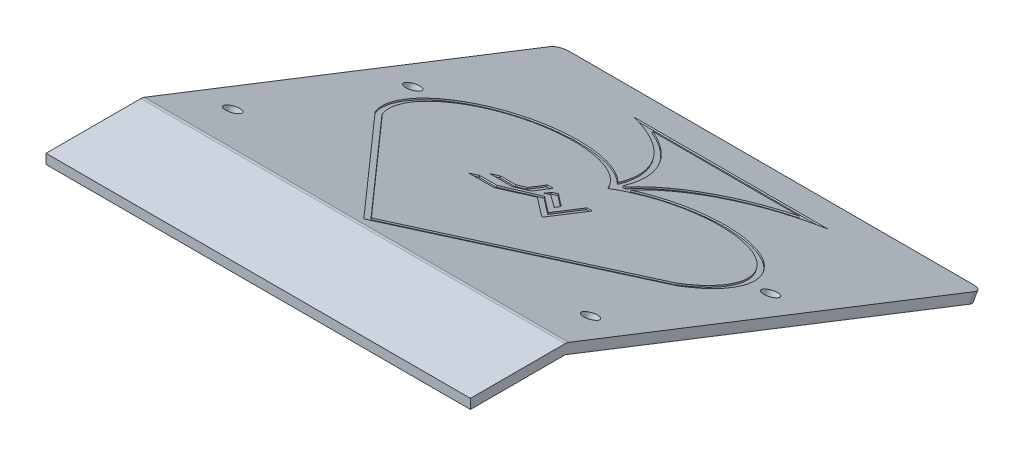
SolidWorks part; units mm, degrees
ref_plane "Plano frontal" through (0, 0, 0) normal (0, 0, 1) x (1, 0, 0)
ref_plane "Plano superior" through (0, 0, 0) normal (0, 1, 0) x (1, 0, 0)
ref_plane "Plano direito" through (0, 0, 0) normal (1, 0, 0) x (0, 0, -1)
sketch "Esboço1" plane through (0, 0, 0) normal (1, 0, 0) x (0, 0, -1)
  line L0 (0, 2) -> (19.99, 2)
  line L1 (19.61, 0) -> (0, 0)
  line L2 (19.99, 2) -> (106.12, -31.7453)
  line L3 (105.11, -33.4985) -> (19.61, 0)
  line L4 (0, 2) -> (0, 0)
  line L5 (106.12, -31.7453) -> (105.11, -33.4985)
  point P6 (0, 0)
  dimension "D1" = 19.61
  dimension "D2" = 19.99
  dimension "D3" = 105.11
  dimension "D4" = 106.12
  dimension "D5" = 2
  dimension "D6" = 31.7453
extrude "Ressalto-extrusão1" add sketch "Esboço1" along normal blind 87.78
sketch "Esboço2" plane through (0, 8.5236, -3.3395) normal (0, 0.9311, -0.3648) x (1, 0, 0)
  circle A0 centre (80.8, 30.5876) radius 1.55 construction
  circle A1 centre (80.8, 30.5876) radius 1.55
  circle A2 centre (6.8, 30.5876) radius 1.55 construction
  circle A3 centre (6.8, 30.5876) radius 1.55
  circle A4 centre (80.8, 70.5876) radius 1.55 construction
  circle A5 centre (80.8, 70.5876) radius 1.55
  circle A6 centre (6.8, 70.5876) radius 1.55 construction
  circle A7 centre (6.8, 70.5876) radius 1.55
extrude "Corte-extrusão1" cut sketch "Esboço2" against normal up to surface (2.0008 mm away) up to face at (43.89, -16.7493, -62.36)
fillet "Filete1" radius 2 2 edges at (0, -32.6219, -105.615) (87.78, -32.6219, -105.615)
fillet "Filete2" radius 2 1 edges at (43.89, 2, -19.99)
sketch "Esboço4" plane through (0, 8.5236, -3.3395) normal (0, 0.9311, -0.3648) x (1, 0, 0)
  line L0 (43.89, 21.5519) -> (43.89, 91.5519) construction
  line L1 (99.9585, 56.5537) -> (-12.1785, 56.55) construction
  line L2 (43.89, 21.5519) -> (13.5797, 56.5509)
  line L3 (43.89, 21.5519) -> (74.2015, 56.5529)
  line L4 (59.0454, 100.3019) -> (28.7346, 100.3019)
  line L5 (87.78, -0.7296) -> (0, -0.7296) construction
  line L6 (87.78, -0.7296) -> (0, -0.7296) construction
  line L7 (43.89, -0.7296) -> (43.89, 4.4324) construction
  line L8 (0, 108.3651) -> (0, 18.2607) construction
  line L9 (0, 108.3651) -> (0, 18.2607) construction
  circle A0 centre (43.89, 56.5519) radius 17.5 construction
  circle A1 centre (43.89, 39.0519) radius 17.5 construction
  circle A2 centre (28.7346, 47.8019) radius 17.5 construction
  circle A3 centre (59.0454, 47.8019) radius 17.5 construction
  arc A4 (43.89, 74.0519) -> (13.5797, 56.5509) centre (28.7346, 65.3019) ccw
  arc A5 (74.2015, 56.5529) -> (43.89, 74.0519) centre (59.0454, 65.3019) ccw
  circle A6 centre (28.7346, 30.3019) radius 17.5 construction
  circle A7 centre (59.0454, 30.3019) radius 17.5 construction
  circle A8 centre (43.89, 74.0519) radius 17.5 construction
  circle A9 centre (28.7346, 82.8019) radius 17.5 construction
  circle A10 centre (59.0454, 82.8019) radius 17.5 construction
  arc A11 (59.0454, 100.3019) -> (43.89, 74.0519) centre (74.2009, 74.0519) ccw
  arc A12 (43.89, 74.0519) -> (28.7346, 100.3019) centre (13.5791, 74.0519) ccw
  arc A13 (43.89, 74.0519) -> (43.89, 56.5519) centre (28.7346, 65.3019) cw construction
  arc A14 (28.7346, 47.8019) -> (43.89, 56.5519) centre (28.7346, 65.3019) ccw construction
  arc A15 (43.89, 56.5519) -> (28.7346, 47.8019) centre (28.7346, 65.3019) cw construction
  arc A16 (28.7346, 47.8019) -> (24.7873, 48.2528) centre (28.7346, 65.3019) cw construction
  arc A17 (17.9085, 51.5525) -> (24.7873, 48.2528) centre (28.7346, 65.3019) ccw construction
  arc A18 (24.7873, 48.2528) -> (17.9085, 51.5525) centre (28.7346, 65.3019) cw construction
  arc A19 (17.9085, 51.5525) -> (13.5797, 56.5509) centre (28.7346, 65.3019) cw construction
  arc A20 (13.5797, 56.5509) -> (17.9085, 51.5525) centre (28.7346, 65.3019) ccw construction
  arc A21 (43.89, 56.5519) -> (43.89, 74.0519) centre (28.7346, 65.3019) ccw construction
  arc A22 (43.89, 74.0519) -> (43.89, 56.5519) centre (59.0454, 65.3019) ccw construction
  arc A23 (43.89, 56.5519) -> (59.0454, 47.8019) centre (59.0454, 65.3019) ccw construction
  arc A24 (59.0454, 47.8019) -> (69.87, 51.5512) centre (59.0454, 65.3019) ccw construction
  arc A25 (69.87, 51.5512) -> (74.2015, 56.5529) centre (59.0454, 65.3019) ccw construction
  point P4 (43.89, 56.5519)
  point P28 (13.5797, 56.5509)
  point P34 (43.89, 56.5519)
  point P35 (74.2015, 56.5529)
  dimension "D2" = 35
  dimension "D1" = 70
  dimension "D3" = 57.28
sketch "Esboço5" plane through (0, 8.5236, -3.3395) normal (0, 0.9311, -0.3648) x (1, 0, 0)
  line L0 (59.0454, 100.3019) -> (28.7346, 100.3019) construction
  line L1 (43.89, 21.5519) -> (74.2015, 56.5529) construction
  line L2 (43.89, 21.5519) -> (13.5797, 56.5509) construction
  line L3 (59.0454, 100.3019) -> (28.7346, 100.3019)
  line L4 (43.89, 21.5519) -> (74.2015, 56.5529)
  line L5 (43.89, 21.5519) -> (13.5797, 56.5509)
  line L6 (43.89, 19.8716) -> (12.6806, 55.9088)
  line L7 (43.89, 19.8716) -> (75.1006, 55.9109)
  line L8 (63.9416, 101.4019) -> (23.8384, 101.4019)
  line L9 (59.0454, 101.4019) -> (28.7346, 101.4019) construction
  line L10 (43.6636, 77.75) -> (44.1164, 77.75)
  arc A0 (43.89, 74.0519) -> (28.7346, 100.3019) centre (13.5791, 74.0519) ccw construction
  arc A1 (59.0454, 100.3019) -> (43.89, 74.0519) centre (74.2009, 74.0519) ccw construction
  arc A2 (74.2015, 56.5529) -> (43.89, 74.0519) centre (59.0454, 65.3019) ccw construction
  arc A3 (43.89, 74.0519) -> (13.5797, 56.5509) centre (28.7346, 65.3019) ccw construction
  arc A4 (43.6636, 77.75) -> (28.7346, 100.3019) centre (13.5791, 74.0519) ccw
  arc A5 (59.0454, 100.3019) -> (44.1164, 77.75) centre (74.2009, 74.0519) ccw
  arc A6 (74.2015, 56.5529) -> (43.89, 74.0519) centre (59.0454, 65.3019) ccw
  arc A7 (43.89, 74.0519) -> (13.5797, 56.5509) centre (28.7346, 65.3019) ccw
  arc A9 (75.1006, 55.9109) -> (45.225, 77.75) centre (59.0454, 65.3019) ccw
  arc A10 (42.555, 77.75) -> (23.8384, 101.4019) centre (13.5791, 74.0519) ccw
  arc A11 (63.9416, 101.4019) -> (45.225, 77.75) centre (74.2009, 74.0519) ccw
  arc A12 (59.5954, 99.3492) -> (44.99, 74.0519) centre (74.2009, 74.0519) ccw construction
  arc A13 (42.79, 74.0519) -> (28.1846, 99.3492) centre (13.5791, 74.0519) ccw construction
  arc A14 (43.89, 74.0519) -> (28.7346, 100.3019) centre (13.5791, 74.0519) ccw construction
  arc A15 (59.0454, 100.3019) -> (43.89, 74.0519) centre (74.2009, 74.0519) ccw construction
  arc A17 (75.1006, 55.9109) -> (43.89, 76.0848) centre (59.0454, 65.3019) ccw construction
  arc A18 (42.555, 77.75) -> (12.6806, 55.9088) centre (28.7346, 65.3019) ccw
  arc A19 (43.89, 76.0848) -> (12.6806, 55.9088) centre (28.7346, 65.3019) ccw construction
  dimension "D2" = 60.6218
  dimension "D3" = 1.1
  dimension "D4" = 1.1
  dimension "D1" = 1.1
  dimension "D5" = 1.1
extrude "Corte-extrusão2" cut sketch "Esboço5" against normal blind 0.3 contours A10 A18 L6 L7 A9 A11 L8 L3 A5 L10 A4 A7 A6 L4 L5
sketch "Logo_MF" plane through (0, 8.5236, -3.3395) normal (0, 0.9311, -0.3648) x (1, 0, 0)
  line L0 (49.9626, 64.155) -> (48.829, 64.155)
  line L1 (48.829, 64.155) -> (48.829, 55.5351)
  line L2 (48.829, 55.5351) -> (43.89, 60.0216)
  line L3 (43.89, 60.0216) -> (38.9069, 54.7788)
  line L4 (38.9069, 54.7788) -> (35.3881, 54.7788)
  line L5 (35.3881, 54.7788) -> (34.2601, 53.537)
  line L6 (34.2601, 53.537) -> (39.4506, 53.537)
  line L7 (39.4506, 53.537) -> (43.8882, 58.4222)
  line L8 (43.8882, 58.4222) -> (49.9626, 52.9043)
  line L9 (49.9626, 52.9043) -> (49.9626, 64.155)
  line L10 (47.5203, 58.2743) -> (47.5203, 59.8448)
  line L11 (47.5203, 59.8448) -> (43.6399, 63.3698)
  line L12 (43.6399, 63.3698) -> (42.959, 62.6202)
  line L13 (42.959, 62.6202) -> (42.959, 60.9001)
  line L14 (42.959, 60.9001) -> (43.641, 61.6509)
  line L15 (43.641, 61.6509) -> (47.5203, 58.2743)
  line L16 (41.859, 64.155) -> (41.859, 59.313)
  line L17 (41.859, 59.313) -> (39.859, 57.2088)
  line L18 (39.859, 57.2088) -> (35.1755, 57.2088)
  line L19 (35.1755, 57.2088) -> (36.3279, 58.4212)
  line L20 (36.3279, 58.4212) -> (39.4501, 58.4212)
  line L21 (39.4501, 58.4212) -> (40.644, 59.6773)
  line L22 (40.644, 59.6773) -> (40.644, 64.155)
  line L23 (40.644, 64.155) -> (41.859, 64.155)
  line L24 (43.89, 74.0519) -> (43.89, 21.5519) construction
  line L25 (0, 108.3651) -> (0, 18.2607) construction
  line L26 (0, 18.2607) -> (87.78, 18.2607) construction
  dimension "D1" = 2.43
  dimension "D2" = 6.97
  dimension "D3" = 1.1
  dimension "D4" = 34.2601
  dimension "D5" = 35.1755
  dimension "D6" = 35.3881
  dimension "D7" = 36.3279
  dimension "D8" = 38.9069
  dimension "D9" = 39.4501
  dimension "D10" = 39.4506
  dimension "D11" = 39.859
  dimension "D12" = 40.644
  dimension "D13" = 41.859
  dimension "D14" = 47.5203
  dimension "D15" = 43.6399
  dimension "D16" = 43.641
  dimension "D17" = 43.8882
  dimension "D18" = 43.89
  dimension "D19" = 49.9626
  dimension "D20" = 34.6436
  dimension "D21" = 87.78
  dimension "D22" = 35.2763
  dimension "D23" = 37.2745
  dimension "D24" = 41.5842
  dimension "D25" = 40.0137
  dimension "D26" = 42.6394
  dimension "D27" = 45.8944
  dimension "D37" = 90.1044
extrude "Corte-extrusão3" cut sketch "Logo_MF" against normal blind 0.3
